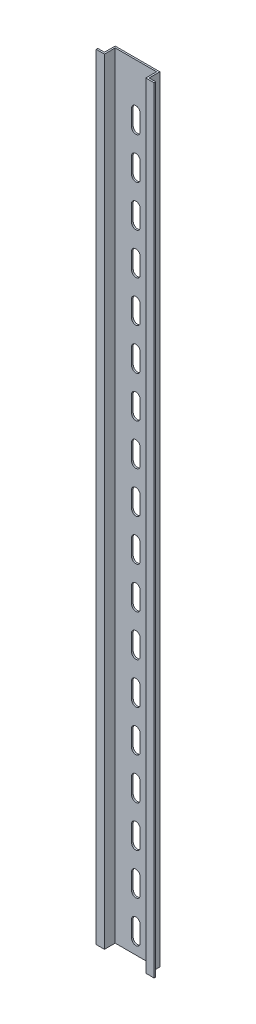
SolidWorks part; units mm, degrees
ref_plane "Front Plane" through (0, 0, 0) normal (0, 0, 1) x (1, 0, 0)
ref_plane "Top Plane" through (0, 0, 0) normal (0, 1, 0) x (1, 0, 0)
ref_plane "Right Plane" through (0, 0, 0) normal (1, 0, 0) x (0, 0, -1)
sketch "Sketch1" plane through (0, 0, 0) normal (0, 1, 0) x (1, 0, 0)
  line L0 (-13.5, 0) -> (13.5, 0)
  line L1 (13.5, 0) -> (13.5, -6.5)
  line L2 (13.5, -6.5) -> (17.5, -6.5)
  line L3 (17.5, -6.5) -> (17.5, -7.5)
  line L4 (17.5, -7.5) -> (12.5, -7.5)
  line L5 (12.5, -7.5) -> (12.5, -1)
  line L6 (12.5, -1) -> (-12.5, -1)
  line L7 (-12.5, -1) -> (-12.5, -7.5)
  line L8 (-12.5, -7.5) -> (-17.5, -7.5)
  line L9 (-17.5, -7.5) -> (-17.5, -6.5)
  line L10 (-17.5, -6.5) -> (-13.5, -6.5)
  line L11 (-13.5, -6.5) -> (-13.5, 0)
extrude "Rail" add sketch "Sketch1" along normal blind 469
sketch "Sketch2" plane through (0, 0, 0) normal (0, 0, 1) x (1, 0, 0)
  line L0 (0, 7.6) -> (0, 17.4) construction
  line L1 (-2.6, 7.6) -> (-2.6, 17.4)
  line L2 (2.6, 7.6) -> (2.6, 17.4)
  line L3 (0, 32.6) -> (0, 42.4) construction
  line L4 (-2.6, 32.6) -> (-2.6, 42.4)
  line L5 (2.6, 32.6) -> (2.6, 42.4)
  line L6 (0, 57.6) -> (0, 67.4) construction
  line L7 (-2.6, 57.6) -> (-2.6, 67.4)
  line L8 (2.6, 57.6) -> (2.6, 67.4)
  line L9 (0, 82.6) -> (0, 92.4) construction
  line L10 (-2.6, 82.6) -> (-2.6, 92.4)
  line L11 (2.6, 82.6) -> (2.6, 92.4)
  line L12 (0, 107.6) -> (0, 117.4) construction
  line L13 (-2.6, 107.6) -> (-2.6, 117.4)
  line L14 (2.6, 107.6) -> (2.6, 117.4)
  line L15 (0, 132.6) -> (0, 142.4) construction
  line L16 (-2.6, 132.6) -> (-2.6, 142.4)
  line L17 (2.6, 132.6) -> (2.6, 142.4)
  line L18 (0, 157.6) -> (0, 167.4) construction
  line L19 (-2.6, 157.6) -> (-2.6, 167.4)
  line L20 (2.6, 157.6) -> (2.6, 167.4)
  line L21 (0, 182.6) -> (0, 192.4) construction
  line L22 (-2.6, 182.6) -> (-2.6, 192.4)
  line L23 (2.6, 182.6) -> (2.6, 192.4)
  line L24 (0, 207.6) -> (0, 217.4) construction
  line L25 (-2.6, 207.6) -> (-2.6, 217.4)
  line L26 (2.6, 207.6) -> (2.6, 217.4)
  line L27 (0, 232.6) -> (0, 242.4) construction
  line L28 (-2.6, 232.6) -> (-2.6, 242.4)
  line L29 (2.6, 232.6) -> (2.6, 242.4)
  line L30 (0, 257.6) -> (0, 267.4) construction
  line L31 (-2.6, 257.6) -> (-2.6, 267.4)
  line L32 (2.6, 257.6) -> (2.6, 267.4)
  line L33 (0, 282.6) -> (0, 292.4) construction
  line L34 (-2.6, 282.6) -> (-2.6, 292.4)
  line L35 (2.6, 282.6) -> (2.6, 292.4)
  line L36 (0, 307.6) -> (0, 317.4) construction
  line L37 (-2.6, 307.6) -> (-2.6, 317.4)
  line L38 (2.6, 307.6) -> (2.6, 317.4)
  line L39 (0, 332.6) -> (0, 342.4) construction
  line L40 (-2.6, 332.6) -> (-2.6, 342.4)
  line L41 (2.6, 332.6) -> (2.6, 342.4)
  line L42 (0, 357.6) -> (0, 367.4) construction
  line L43 (-2.6, 357.6) -> (-2.6, 367.4)
  line L44 (2.6, 357.6) -> (2.6, 367.4)
  line L45 (0, 382.6) -> (0, 392.4) construction
  line L46 (-2.6, 382.6) -> (-2.6, 392.4)
  line L47 (2.6, 382.6) -> (2.6, 392.4)
  line L48 (0, 407.6) -> (0, 417.4) construction
  line L49 (-2.6, 407.6) -> (-2.6, 417.4)
  line L50 (2.6, 407.6) -> (2.6, 417.4)
  line L51 (0, 432.6) -> (0, 442.4) construction
  line L52 (-2.6, 432.6) -> (-2.6, 442.4)
  line L53 (2.6, 432.6) -> (2.6, 442.4)
  arc A0 (-2.6, 7.6) -> (2.6, 7.6) centre (0, 7.6) ccw
  arc A1 (2.6, 17.4) -> (-2.6, 17.4) centre (0, 17.4) ccw
  arc A2 (-2.6, 32.6) -> (2.6, 32.6) centre (0, 32.6) ccw
  arc A3 (2.6, 42.4) -> (-2.6, 42.4) centre (0, 42.4) ccw
  arc A4 (-2.6, 57.6) -> (2.6, 57.6) centre (0, 57.6) ccw
  arc A5 (2.6, 67.4) -> (-2.6, 67.4) centre (0, 67.4) ccw
  arc A6 (-2.6, 82.6) -> (2.6, 82.6) centre (0, 82.6) ccw
  arc A7 (2.6, 92.4) -> (-2.6, 92.4) centre (0, 92.4) ccw
  arc A8 (-2.6, 107.6) -> (2.6, 107.6) centre (0, 107.6) ccw
  arc A9 (2.6, 117.4) -> (-2.6, 117.4) centre (0, 117.4) ccw
  arc A10 (-2.6, 132.6) -> (2.6, 132.6) centre (0, 132.6) ccw
  arc A11 (2.6, 142.4) -> (-2.6, 142.4) centre (0, 142.4) ccw
  arc A12 (-2.6, 157.6) -> (2.6, 157.6) centre (0, 157.6) ccw
  arc A13 (2.6, 167.4) -> (-2.6, 167.4) centre (0, 167.4) ccw
  arc A14 (-2.6, 182.6) -> (2.6, 182.6) centre (0, 182.6) ccw
  arc A15 (2.6, 192.4) -> (-2.6, 192.4) centre (0, 192.4) ccw
  arc A16 (-2.6, 207.6) -> (2.6, 207.6) centre (0, 207.6) ccw
  arc A17 (2.6, 217.4) -> (-2.6, 217.4) centre (0, 217.4) ccw
  arc A18 (-2.6, 232.6) -> (2.6, 232.6) centre (0, 232.6) ccw
  arc A19 (2.6, 242.4) -> (-2.6, 242.4) centre (0, 242.4) ccw
  arc A20 (-2.6, 257.6) -> (2.6, 257.6) centre (0, 257.6) ccw
  arc A21 (2.6, 267.4) -> (-2.6, 267.4) centre (0, 267.4) ccw
  arc A22 (-2.6, 282.6) -> (2.6, 282.6) centre (0, 282.6) ccw
  arc A23 (2.6, 292.4) -> (-2.6, 292.4) centre (0, 292.4) ccw
  arc A24 (-2.6, 307.6) -> (2.6, 307.6) centre (0, 307.6) ccw
  arc A25 (2.6, 317.4) -> (-2.6, 317.4) centre (0, 317.4) ccw
  arc A26 (-2.6, 332.6) -> (2.6, 332.6) centre (0, 332.6) ccw
  arc A27 (2.6, 342.4) -> (-2.6, 342.4) centre (0, 342.4) ccw
  arc A28 (-2.6, 357.6) -> (2.6, 357.6) centre (0, 357.6) ccw
  arc A29 (2.6, 367.4) -> (-2.6, 367.4) centre (0, 367.4) ccw
  arc A30 (-2.6, 382.6) -> (2.6, 382.6) centre (0, 382.6) ccw
  arc A31 (2.6, 392.4) -> (-2.6, 392.4) centre (0, 392.4) ccw
  arc A32 (-2.6, 407.6) -> (2.6, 407.6) centre (0, 407.6) ccw
  arc A33 (2.6, 417.4) -> (-2.6, 417.4) centre (0, 417.4) ccw
  arc A34 (-2.6, 432.6) -> (2.6, 432.6) centre (0, 432.6) ccw
  arc A35 (2.6, 442.4) -> (-2.6, 442.4) centre (0, 442.4) ccw
  point P3 (0, 12.5)
  point P8 (0, 37.5)
  point P15 (0, 62.5)
  point P22 (0, 87.5)
  point P29 (0, 112.5)
  point P36 (0, 137.5)
  point P43 (0, 162.5)
  point P50 (0, 187.5)
  point P57 (0, 212.5)
  point P64 (0, 237.5)
  point P71 (0, 262.5)
  point P78 (0, 287.5)
  point P85 (0, 312.5)
  point P92 (0, 337.5)
  point P99 (0, 362.5)
  point P106 (0, 387.5)
  point P113 (0, 412.5)
  point P120 (0, 437.5)
  point P127 (0, 0)
extrude "Slots" cut sketch "Sketch2" against normal through all and the other way through all
